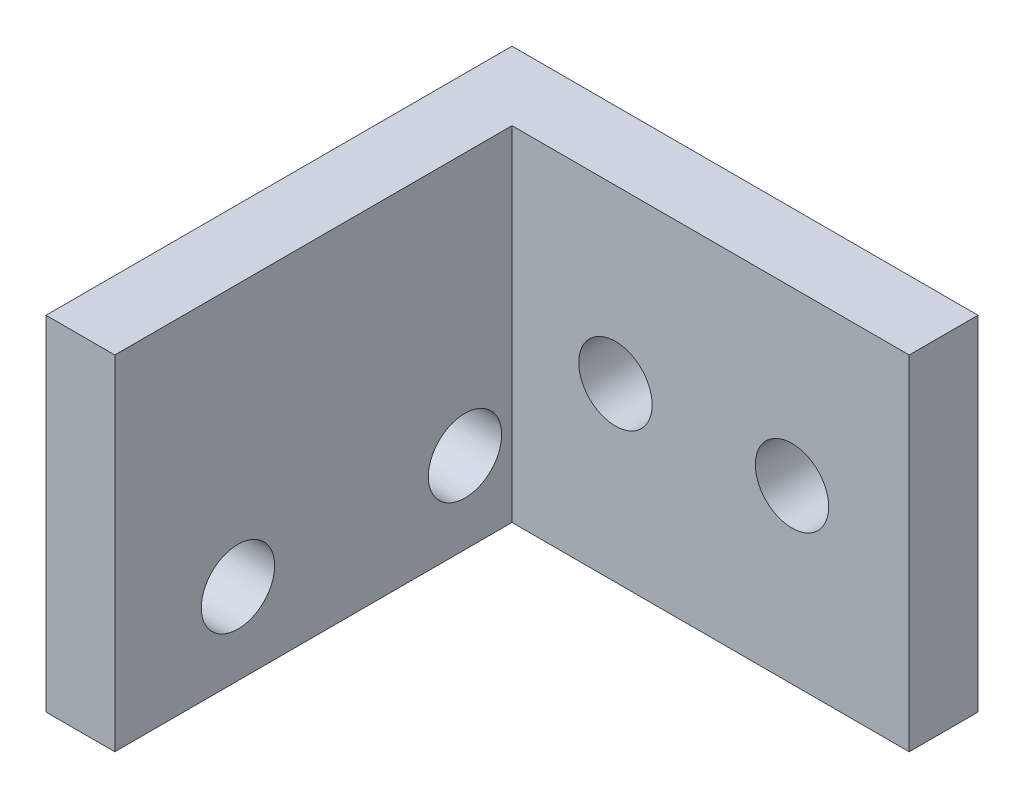
SolidWorks part; units mm, degrees
ref_plane "Front" through (0, 0, 0) normal (0, 0, 1) x (1, 0, 0)
ref_plane "Top" through (0, 0, 0) normal (0, 1, 0) x (1, 0, 0)
ref_plane "Right" through (0, 0, 0) normal (1, 0, 0) x (0, 0, -1)
sketch "Sketch1" plane through (0, 0, 0) normal (0, 1, 0) x (1, 0, 0)
  line L0 (0, 0) -> (0, 20.32)
  line L1 (0, 20.32) -> (20.32, 20.32)
  line L2 (20.32, 20.32) -> (20.32, 17.32)
  line L3 (20.32, 17.32) -> (3, 17.32)
  line L4 (3, 17.32) -> (3, 0)
  line L5 (3, 0) -> (0, 0)
  dimension "D1" = 20.32
  dimension "D2" = 20.32
  dimension "D3" = 3
  dimension "D4" = 3
extrude "Boss-Extrude1" add sketch "Sketch1" along normal blind 14.986
sketch "Sketch2" plane through (0, 0, 0) normal (-1, 0, 0) x (0, 0, 1)
  circle A0 centre (-5.37, 3.55) radius 1.6
  circle A1 centre (-15.27, 3.55) radius 1.6
extrude "Cut-Extrude1" cut sketch "Sketch2" against normal blind 25
sketch "Sketch4" plane through (0, 0, -17.32) normal (0, 0, 1) x (1, 0, 0)
  line L0 (3, 14.986) -> (20.32, 14.986) construction
  circle A0 centre (7.5102, 7.496) radius 1.6
  circle A1 centre (15.2088, 7.493) radius 1.6
  dimension "D1" = 7.493
  dimension "D2" = 3.2
  dimension "D3" = 7.49
extrude "Cut-Extrude2" cut sketch "Sketch4" against normal blind 25
